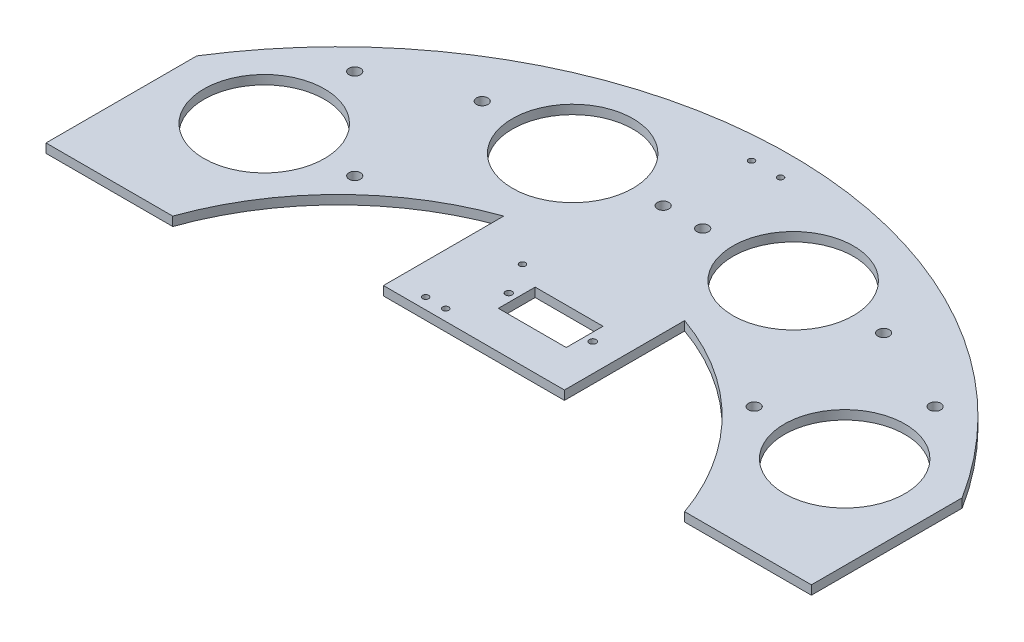
SolidWorks part; units mm, degrees
ref_plane "Front Plane" through (0, 0, 0) normal (0, 0, 1) x (1, 0, 0)
ref_plane "Top Plane" through (0, 0, 0) normal (0, 1, 0) x (1, 0, 0)
ref_plane "Right Plane" through (0, 0, 0) normal (1, 0, 0) x (0, 0, -1)
sketch "Sketch2" [suppressed] plane through (0, 0, 0) normal (0, 1, 0) x (1, 0, 0)
  line L0 (-25, 150) -> (25, 150)
  line L1 (-25, 0) -> (-25, 150) construction
  line L2 (0, 0) -> (-37.08, 101.61) construction
  line L3 (0, 0) -> (-82.9172, 69.4568) construction
  arc A0 (-25, 150) -> (0, -147.902) centre (-25, 0) ccw
  arc A1 (0, -147.902) -> (25, 150) centre (25, 0) ccw
  circle A2 centre (-37.08, 101.61) radius 20
  circle A3 centre (-82.9172, 69.4568) radius 20
  circle A4 centre (-106.5368, 18.6928) radius 20
  dimension "D1" = 300
  dimension "D2" = 300
  dimension "D5" = 40
  dimension "D3" = 50
  dimension "D4" = 25
  dimension "D6" = 12.08
  dimension "D7" = 48.39
  dimension "D9" = 30
sketch "Sketch3" plane through (0, 0, 0) normal (0, 1, 0) x (1, 0, 0)
  line L0 (-126.8858, -16.7898) -> (-84.8717, -16.7898)
  line L5 (0, 43.228) -> (0, -1.7898) construction
  line L6 (-175, -125) -> (-139.6509, -99.7506) construction
  line L7 (-36.5556, 67.5067) -> (-27.2905, 38.9915) construction
  line L8 (-96.2239, 24.9107) -> (-71.9654, 7.2859) construction
  line L9 (-90.0178, -46.7898) -> (0, -46.7898) construction
  line L10 (0, -55) -> (0, 55) construction
  line L11 (-175, -16.7898) -> (-146.9694, -16.7898)
  line L12 (-126.8858, -16.7898) -> (-126.8858, 33.2102)
  line L13 (126.8858, -16.7898) -> (126.8858, 33.2102)
  line L14 (0, 0) -> (0, 43.228) construction
  line L15 (-30, -1.7898) -> (30, -1.7898)
  line L16 (30, -1.7898) -> (30, 38.0819)
  line L17 (-19.0404, 13.6003) -> (-17.289, 8.2102) construction
  line L18 (-30, -1.7898) -> (-30, 38.0819)
  line L20 (84.8717, -16.7898) -> (126.8858, -16.7898)
  line L21 (-11.8672, -8.4766) -> (-9.166, -16.7898) construction
  circle A0 centre (-36.5556, 67.5067) radius 20
  circle A1 centre (-96.2239, 24.9107) radius 20
  circle A3 centre (36.5556, 67.5067) radius 20
  circle A4 centre (96.2239, 24.9107) radius 20
  arc A8 (84.8717, -16.7898) -> (-84.8717, -16.7898) centre (0, -46.7898) ccw
  arc A9 (126.8858, 33.2102) -> (-126.8858, 33.2102) centre (0, -46.7898) ccw
  point P0 (0, 0)
  point P10 (0, -46.7898)
  point P33 (0, -1.7898)
  point P40 (-30, 38.0819)
  point P41 (30, 38.0819)
  dimension "D3" = 40
  dimension "D7" = 40
  dimension "D4" = 90.0178
  dimension "D5" = 150
  dimension "D6" = 120
  dimension "D9" = 36
  dimension "D10" = 36
  dimension "D12" = 120
  dimension "D15" = 30
  dimension "D16" = 50
  dimension "D2" = 18
  dimension "D11" = 60
  dimension "D13" = 46.7898
  dimension "D8" = 15
extrude "Boss-Extrude3" add sketch "Sketch3" along normal blind 3
hole_wizard "#10-24 Tapped Hole1" positions "Sketch4" profile "Sketch5" tap size "#10-24" standard "ANSI Inch" end condition through all
sketch "Sketch4" plane through (0, 3, 0) normal (0, 1, 0) x (1, 0, 0)
  point P0 (-66.2239, 24.9107)
  point P2 (-96.2239, 54.9107)
  point P4 (-66.5556, 67.5067)
  point P6 (-6.5556, 67.5067)
  point P8 (6.5556, 67.5067)
  point P10 (66.5556, 67.5067)
  point P12 (96.2239, 54.9107)
  point P14 (66.2239, 24.9107)
  dimension "D1" = 30
  dimension "D2" = 30
  dimension "D3" = 30
  dimension "D4" = 30
  dimension "D5" = 30
  dimension "D6" = 30
  dimension "D7" = 30
  dimension "D8" = 30
sketch "Sketch5" plane through (-66.2239, 3, -24.9107) normal (1, 0, 0) x (0, 0, 1)
  line L0 (0, 0) -> (0, 3)
  line L1 (0, 3) -> (1.8986, 3)
  line L2 (1.8986, 3) -> (1.8986, 0)
  line L5 (1.8986, 0) -> (0, 0)
  line L11 (0, -6.35) -> (0, 107.95) construction
  dimension "Thru Tap Drill Dia." = 3.7973
  dimension "Thru Tap Drill Depth" = 3
cosmetic thread "Hole Thread1" parameters "D2"=4.826
cosmetic thread "Hole Thread2" parameters "D2"=4.826
cosmetic thread "Hole Thread3" parameters "D2"=4.826
cosmetic thread "Hole Thread4" parameters "D2"=4.826
cosmetic thread "Hole Thread5" parameters "D2"=4.826
cosmetic thread "Hole Thread6" parameters "D2"=4.826
cosmetic thread "Hole Thread7" parameters "D2"=4.826
cosmetic thread "Hole Thread8" parameters "D2"=4.826
sketch "Sketch6" plane through (0, 0, 0) normal (0, -1, 0) x (1, 0, 0)
  line L0 (18.1, -10.7102) -> (-4.4, -10.7102)
  line L1 (-4.4, -10.7102) -> (-4.4, -22.9102)
  line L2 (-4.4, -22.9102) -> (18.1, -22.9102)
  line L3 (18.1, -22.9102) -> (18.1, -10.7102)
  line L4 (18.1, -22.0602) -> (18.1, -11.5602) construction
  line L5 (17.25, -10.7102) -> (-3.55, -10.7102) construction
  line L6 (-4.4, -11.5602) -> (-4.4, -22.0602) construction
  line L7 (-3.55, -22.9102) -> (17.25, -22.9102) construction
extrude "Cut-Extrude1" cut sketch "Sketch6" against normal up to surface (3 mm away) up to face at (-66.2239, 3, -23.0121)
sketch "Sketch7" plane through (0, 0, 0) normal (0, -1, 0) x (1, 0, 0)
  circle A0 centre (-13.0537, -1.9107) radius 1
  circle A1 centre (-19.7021, -1.9107) radius 1
  circle A2 centre (-13.0537, -27.3604) radius 1
  circle A3 centre (-4.805, -95.0641) radius 1
  circle A4 centre (4.805, -95.0641) radius 1
  circle A5 centre (-7.05, -16.8102) radius 1.1
  circle A6 centre (20.7547, -16.8322) radius 1.1226
extrude "Cut-Extrude2" cut sketch "Sketch7" against normal through all
equation "\"D2@Sketch2\"=\"D1@Sketch2\""
equation "\"D7@Sketch3\"=\"D3@Sketch3\""
equation "\"D2@Sketch4\"=\"D1@Sketch4\""
equation "\"D3@Sketch4\"=\"D1@Sketch4\""
equation "\"D4@Sketch4\"=\"D1@Sketch4\""
equation "\"D5@Sketch4\"=\"D1@Sketch4\""
equation "\"D6@Sketch4\"=\"D1@Sketch4\""
equation "\"D7@Sketch4\"=\"D1@Sketch4\""
equation "\"D8@Sketch4\"=\"D1@Sketch4\""
